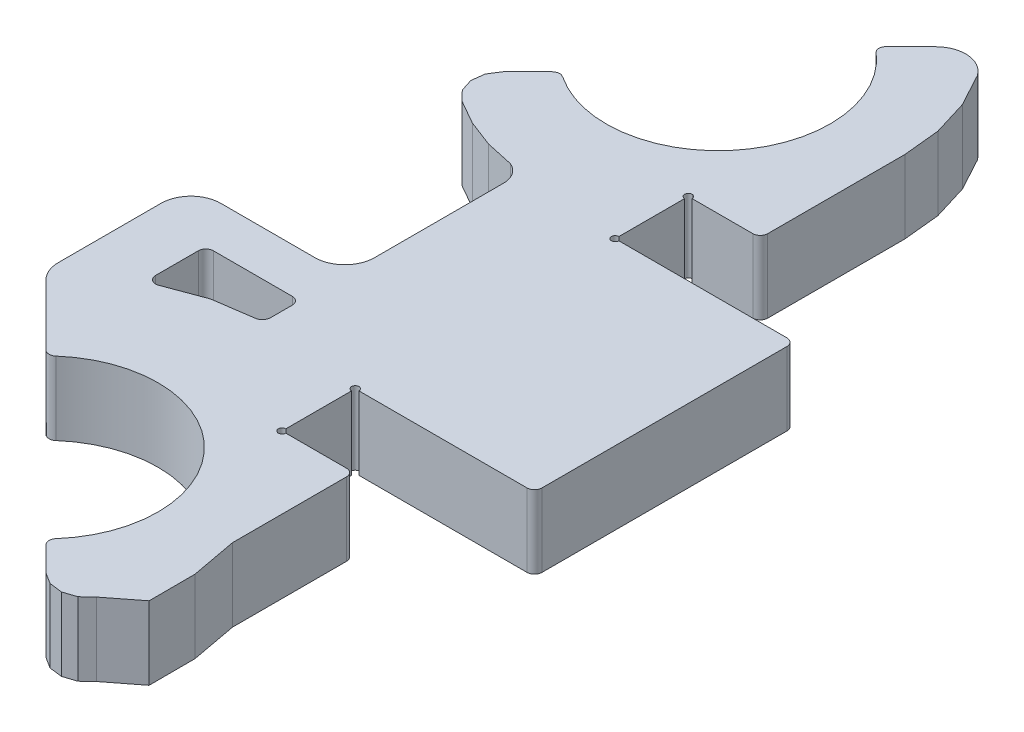
SolidWorks part; units mm, degrees
ref_plane "Plan de face" through (0, 0, 0) normal (0, 0, 1) x (1, 0, 0)
ref_plane "Plan de dessus" through (0, 0, 0) normal (0, 1, 0) x (1, 0, 0)
ref_plane "Plan de droite" through (0, 0, 0) normal (1, 0, 0) x (0, 0, -1)
ref_plane "Plan1" through (0, 0, 0) normal (0, -1, 0) x (1, 0, 0)
sketch "Esquisse1" plane through (0, 0, 0) normal (0, -1, 0) x (1, 0, 0)
  line L0 (-0.8153, 41.1207) -> (-0.8153, 34.2491)
  line L4 (1.1847, 32.2491) -> (7.4847, 32.2491)
  line L8 (9.4847, 30.2491) -> (9.4847, 21.6105)
  line L12 (8.5759, 20.255) -> (6.7236, 19.8519)
  line L13 (6.7236, 19.8519) -> (4.9536, 19.1734)
  line L14 (4.9536, 19.1734) -> (3.3066, 18.2351)
  line L15 (3.3066, 18.2351) -> (2.7065, 17.5995)
  line L16 (2.7065, 17.5995) -> (2.4347, 16.7687)
  line L17 (2.4347, 16.7687) -> (2.5432, 15.9014)
  line L18 (2.5432, 15.9014) -> (3.0113, 15.1632)
  line L19 (3.0113, 15.1632) -> (4.6542, 13.5203)
  line L20 (4.6542, 13.5203) -> (4.8683, 13.3937)
  line L21 (4.8683, 13.3937) -> (5.1169, 13.3859)
  line L22 (5.1169, 13.3859) -> (5.3385, 13.4989)
  line L23 (16.6878, 43.3991) -> (15.8005, 43.3991) construction
  line L24 (16.4378, 43.1491) -> (16.4378, 42.7015) construction
  line L25 (16.4378, 38.7491) -> (16.4378, 36.3669) construction
  line L26 (16.6878, 38.4991) -> (15.8005, 38.4991) construction
  line L27 (16.6878, 21.0991) -> (15.731, 21.0991) construction
  line L28 (16.4378, 20.8491) -> (16.4378, 20.4198) construction
  line L29 (16.4378, 16.4491) -> (16.4378, 14.1929) construction
  line L30 (16.6878, 16.1991) -> (15.8005, 16.1991) construction
  line L31 (9.4847, 52.2491) -> (9.4847, 7.2491) construction
  line L37 (14.3989, 0.8806) -> (16.0418, -0.7623)
  line L42 (19.1137, -0.467) -> (20.2866, 1.7067)
  line L43 (20.2866, 1.7067) -> (21.0091, 4.0685)
  line L44 (21.0091, 4.0685) -> (21.2531, 6.5264)
  line L45 (21.2531, 6.5264) -> (21.2531, 15.6991)
  line L49 (20.7531, 16.1991) -> (16.6878, 16.1991)
  line L59 (16.4378, 16.4491) -> (16.4378, 20.8491)
  line L69 (16.6878, 21.0991) -> (27.9378, 21.0991)
  line L73 (28.4378, 21.5991) -> (28.4378, 37.9991)
  line L77 (27.9378, 38.4991) -> (16.6878, 38.4991)
  line L87 (16.4378, 38.7491) -> (16.4378, 43.1491)
  line L97 (16.6878, 43.3991) -> (20.7531, 43.3991)
  line L101 (21.2531, 43.8991) -> (21.2531, 51.5264)
  line L102 (21.2531, 51.5264) -> (21.8244, 54.6096)
  line L103 (21.8244, 54.6096) -> (21.8334, 57.6942)
  line L104 (21.8334, 57.6942) -> (19.8453, 59.2425)
  line L105 (19.8453, 59.2425) -> (19.2097, 59.8427)
  line L106 (19.2097, 59.8427) -> (18.3789, 60.1144)
  line L107 (18.3789, 60.1144) -> (17.5116, 60.0059)
  line L108 (17.5116, 60.0059) -> (16.7733, 59.5378)
  line L109 (16.7733, 59.5378) -> (15.1305, 57.8949)
  line L127 (3.8389, 46.6033) -> (-0.2296, 42.5349)
  line L130 (9.4847, 37.2595) -> (9.4847, 35.7491)
  line L134 (8.9847, 35.2491) -> (3.6847, 35.2491)
  line L138 (3.1847, 35.7491) -> (3.1847, 38.6154)
  line L143 (3.9077, 39.0629) -> (6.3865, 38.1399)
  line L144 (6.3865, 38.1399) -> (9.0039, 37.7591)
  arc A0 (14.3775, 1.5649) -> (5.3385, 13.4989) centre (9.4847, 7.2491) ccw
  arc A1 (4.5232, 46.6247) -> (15.109, 57.2106) centre (9.4847, 52.2491) ccw
  arc A2 (20.7531, 43.3991) -> (21.2531, 43.8991) centre (20.7531, 43.8991) ccw
  arc A3 (27.9378, 38.4991) -> (28.4378, 37.9991) centre (27.9378, 37.9991) cw
  arc A4 (16.6878, 43.3991) -> (16.4378, 43.1491) centre (16.4378, 43.3991) ccw
  arc A5 (16.4378, 38.7491) -> (16.6878, 38.4991) centre (16.4378, 38.4991) ccw
  arc A6 (27.9378, 21.0991) -> (28.4378, 21.5991) centre (27.9378, 21.5991) ccw
  arc A7 (20.7531, 16.1991) -> (21.2531, 15.6991) centre (20.7531, 15.6991) cw
  arc A8 (16.6878, 21.0991) -> (16.4378, 20.8491) centre (16.4378, 21.0991) ccw
  arc A9 (16.4378, 16.4491) -> (16.6878, 16.1991) centre (16.4378, 16.1991) ccw
  arc A10 (9.4847, 21.6105) -> (8.5759, 20.255) centre (8.0193, 21.6105) cw
  arc A11 (7.4847, 32.2491) -> (9.4847, 30.2491) centre (7.4847, 30.2491) cw
  arc A12 (-0.8153, 34.2491) -> (1.1847, 32.2491) centre (1.1847, 34.2491) ccw
  arc A13 (-0.8153, 41.1207) -> (-0.2296, 42.5349) centre (1.1847, 41.1207) cw
  arc A14 (3.1847, 35.7491) -> (3.6847, 35.2491) centre (3.6847, 35.7491) ccw
  arc A15 (3.1847, 38.6154) -> (3.9077, 39.0629) centre (3.6847, 38.6154) cw
  arc A16 (9.0039, 37.7591) -> (9.4847, 37.2595) centre (8.9225, 37.1997) cw
  arc A17 (8.9847, 35.2491) -> (9.4847, 35.7491) centre (8.9847, 35.7491) ccw
  arc A18 (15.109, 57.2106) -> (15.1305, 57.8949) centre (15.484, 57.5413) cw
  arc A19 (3.8389, 46.6033) -> (4.5232, 46.6247) centre (4.1924, 46.2498) cw
  arc A20 (14.3775, 1.5649) -> (14.3989, 0.8806) centre (14.6646, 1.2314) ccw
  arc A21 (16.0418, -0.7623) -> (19.1137, -0.467) centre (17.456, 0.6519) ccw
  dimension "D1" = 15
  dimension "D2" = 15
  dimension "D6" = 6.3
  dimension "D8" = 8.85
  dimension "D12" = 0.25
  dimension "D13" = 0.25
  dimension "D15" = 0.25
  dimension "D16" = 0.25
  dimension "D5" = 9.4847
  dimension "D20" = 0.5
  dimension "D3" = 45
  dimension "D4" = 7.2491
  dimension "D7" = 6.9531
  dimension "D9" = 4.9
  dimension "D10" = 17.4
  dimension "D11" = 4.9
  dimension "D14" = 18.9531
  dimension "D17" = 2.51
  dimension "D18" = 167.853
  dimension "D19" = 98.277
  dimension "D21" = 3
extrude "Boss.-Extru.1" add sketch "Esquisse1" against normal blind 4.9
